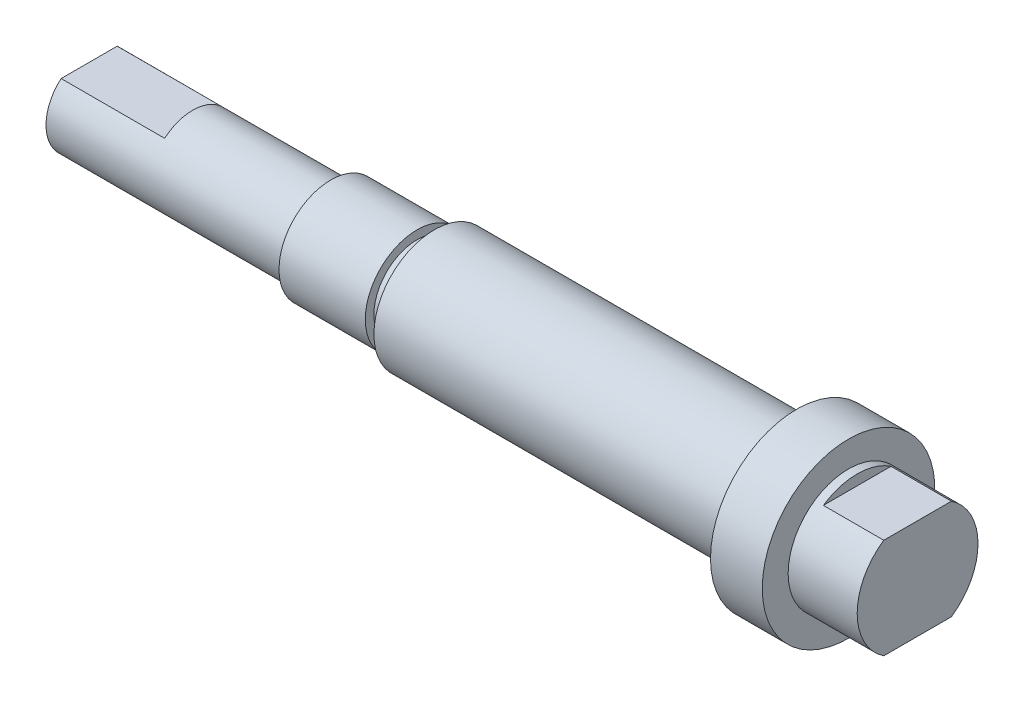
SolidWorks part; units mm, degrees
ref_plane "Front Plane" through (0, 0, 0) normal (0, 0, 1) x (1, 0, 0)
ref_plane "Top Plane" through (0, 0, 0) normal (0, 1, 0) x (1, 0, 0)
ref_plane "Right Plane" through (0, 0, 0) normal (1, 0, 0) x (0, 0, -1)
sketch "Sketch1" plane through (0, 0, 0) normal (1, 0, 0) x (0, 0, -1)
  circle A0 centre (0, 0) radius 3.5
  dimension "D1" = 7
extrude "Boss-Extrude1" add sketch "Sketch1" along normal blind 50
sketch "Sketch2" plane through (50, 0, 0) normal (-1, 0, 0) x (0, 0, 1)
  circle A0 centre (0, 0) radius 5
  dimension "D1" = 10
extrude "Boss-Extrude2" add sketch "Sketch2" along normal blind 3 from offset 6
sketch "Sketch5" plane through (0, 0, 0) normal (-1, 0, 0) x (0, 0, 1)
  circle A1 centre (0, 0) radius 2.5
  circle A2 centre (0, 0) radius 3.5
  circle A3 centre (0, 0) radius 3.5
  dimension "D2" = 5
  dimension "D1" = 0
extrude "Cut-Extrude2" cut sketch "Sketch5" against normal blind 20
sketch "Sketch3" plane through (41, 0, 0) normal (-1, 0, 0) x (0, 0, 1)
  circle A0 centre (0, 0) radius 3
  dimension "D1" = 6
extrude "Boss-Extrude3" add sketch "Sketch3" along normal blind 5 from offset 22
sketch "Sketch6" plane through (50, 0, 0) normal (1, 0, 0) x (0, 0, -1)
  line L0 (-1.9596, 2.9) -> (1.9596, 2.9)
  line L1 (-1.9596, -2.9) -> (1.9596, -2.9)
  circle A0 centre (0, 0) radius 3.5 construction
  circle A1 centre (0, 0) radius 3.5 construction
  circle A2 centre (0, 0) radius 3.5
  point P8 (0, 3.5)
  point P9 (0, -3.5)
  circle M3 centre (0, 0) radius 3.5
  dimension "D1" = 0.6
  dimension "D2" = 0.6
extrude "Cut-Extrude3" cut sketch "Sketch6" against normal blind 5.5 contours L0 M3 | L1 M3
sketch "Sketch7" plane through (50, 0, 0) normal (1, 0, 0) x (0, 0, -1)
  line L2 (1.9596, 2.9) -> (-1.9596, 2.9)
  line L3 (-1.9596, -2.9) -> (1.9596, -2.9)
  line L4 (1.9596, 2.9) -> (-1.9596, 2.9)
  line L5 (-1.9596, -2.9) -> (1.9596, -2.9)
  arc A2 (-1.9596, 2.9) -> (-1.9596, -2.9) centre (0, 0) ccw
  arc A3 (1.9596, -2.9) -> (1.9596, 2.9) centre (0, 0) ccw
  arc A4 (-1.9596, 2.9) -> (-1.9596, -2.9) centre (0, 0) ccw
  arc A5 (1.9596, -2.9) -> (1.9596, 2.9) centre (0, 0) ccw
  dimension "D1" = 0
extrude "Cut-Extrude4" cut sketch "Sketch7" against normal blind 2
sketch "Sketch8" plane through (0, 0, 0) normal (-1, 0, 0) x (0, 0, 1)
  line L0 (-1.6248, 1.9) -> (1.6248, 1.9)
  line L2 (1.6248, -1.9) -> (-1.6248, -1.9)
  circle A0 centre (0, 0) radius 2.5 construction
  circle A1 centre (0, 0) radius 2.5 construction
  circle A2 centre (0, 0) radius 2.5
  point P9 (0, 2.5)
  point P10 (0, -2.5)
  circle M4 centre (0, 0) radius 2.5
  dimension "D1" = 0.6
  dimension "D2" = 0.6
extrude "Cut-Extrude5" cut sketch "Sketch8" against normal blind 6 contours L0 M4 | L2 M4
